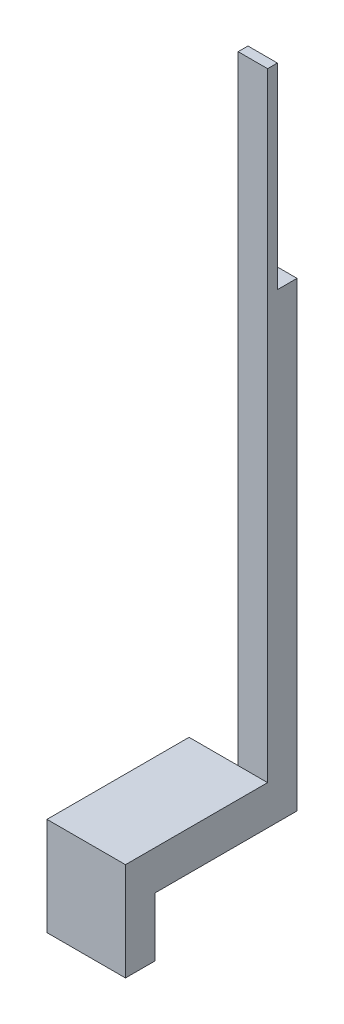
SolidWorks part; units mm, degrees
ref_plane "Alzado" through (0, 0, 0) normal (0, 0, 1) x (1, 0, 0)
ref_plane "Planta" through (0, 0, 0) normal (0, 1, 0) x (1, 0, 0)
ref_plane "Vista lateral" through (0, 0, 0) normal (1, 0, 0) x (0, 0, -1)
sketch "Croquis1" plane through (0, 0, 0) normal (0, 0, 1) x (1, 0, 0)
  line L1 (0, 0) -> (3, 0)
  line L2 (0, 0) -> (0, 47)
  line L3 (0, 47) -> (3, 47)
  line L4 (3, 0) -> (3, 47)
  dimension "D1" = 47
  dimension "D2" = 3
extrude "Saliente-Extruir1" add sketch "Croquis1" along normal blind 3
sketch "Croquis2" plane through (0, 47, 0) normal (0, 1, 0) x (1, 0, 0)
  line L0 (3, -3) -> (3, 0) construction
  line L1 (0, -3) -> (3, -3)
  line L2 (0, -3) -> (0, -2)
  line L3 (0, -2) -> (3, -2)
  line L4 (3, -3) -> (3, -2)
  dimension "D1" = 1
extrude "Saliente-Extruir2" add sketch "Croquis2" along normal blind 20
sketch "Croquis3" plane through (0, 0, 3) normal (0, 0, 1) x (1, 0, 0)
  line L0 (3, 0) -> (3, 67) construction
  line L1 (0, 0) -> (3, 0)
  line L2 (0, 0) -> (0, 4)
  line L3 (0, 4) -> (3, 4)
  line L4 (3, 0) -> (3, 4)
  dimension "D1" = 4
extrude "Saliente-Extruir3" add sketch "Croquis3" along normal blind 11.48
sketch "Croquis4" plane through (0, 4, 0) normal (0, 1, 0) x (1, 0, 0)
  line L0 (3, -14.48) -> (3, -3) construction
  line L1 (0, -14.48) -> (3, -14.48)
  line L2 (0, -14.48) -> (0, -17.48)
  line L3 (0, -17.48) -> (3, -17.48)
  line L4 (3, -14.48) -> (3, -17.48)
  dimension "D1" = 3
extrude "Saliente-Extruir4" add sketch "Croquis4" against normal blind 10
sketch "Croquis5" plane through (0, 0, 0) normal (-1, 0, 0) x (0, 0, 1)
  line L0 (14.48, 0) -> (0, 0) construction
  line L1 (17.48, 4) -> (3, 4) construction
  line L2 (17.48, -6) -> (17.48, 4) construction
  line L3 (14.48, -6) -> (17.48, -6) construction
  line L4 (14.48, -6) -> (14.48, 0) construction
  line L5 (14.48, 0) -> (3, 0)
  line L6 (17.48, 4) -> (3, 4)
  line L7 (17.48, -6) -> (17.48, 4)
  line L8 (14.48, -6) -> (17.48, -6)
  line L9 (14.48, -6) -> (14.48, 0)
  line L10 (3, 4) -> (3, 0)
extrude "Saliente-Extruir5" add sketch "Croquis5" along normal blind 5
